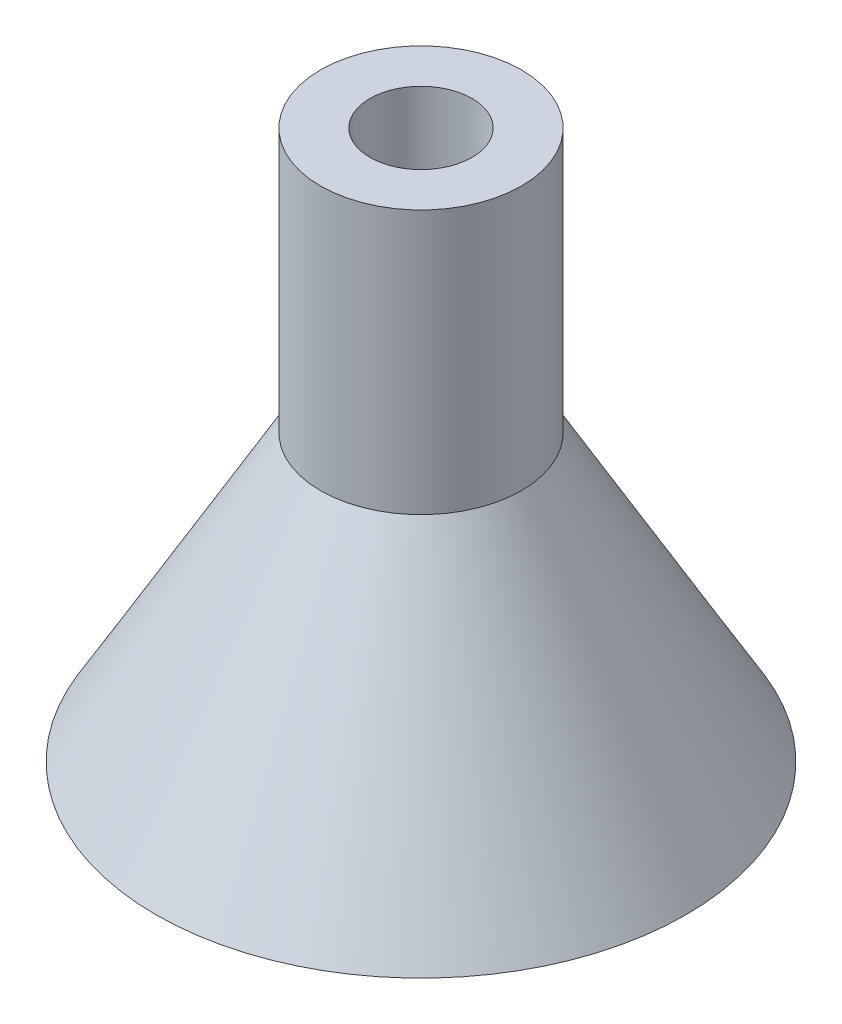
SolidWorks part; units mm, degrees
ref_plane "Front Plane" through (0, 0, 0) normal (0, 0, 1) x (1, 0, 0)
ref_plane "Top Plane" through (0, 0, 0) normal (0, 1, 0) x (1, 0, 0)
ref_plane "Right Plane" through (0, 0, 0) normal (1, 0, 0) x (0, 0, -1)
sketch "Sketch2" plane through (0, 0, 0) normal (0, 0, 1) x (1, 0, 0)
  line L0 (13.0723, 0) -> (16.0745, 0)
  line L1 (16.0745, 0) -> (6.096, 17.2833)
  line L2 (6.096, 17.2833) -> (6.096, 33.2833)
  line L3 (6.096, 33.2833) -> (3.096, 33.2833)
  line L4 (3.096, 33.2833) -> (3.096, 17.2795)
  line L5 (3.096, 17.2795) -> (13.0723, 0)
  line L6 (0, 0) -> (0, 50000) construction
  line L7 (-3.096, 17.2795) -> (-13.0723, 0) construction
  line L8 (-3.096, 33.2833) -> (-3.096, 17.2795) construction
  line L9 (-6.096, 33.2833) -> (-3.096, 33.2833) construction
  line L10 (-6.096, 17.2833) -> (-6.096, 33.2833) construction
  line L11 (-16.0745, 0) -> (-6.096, 17.2833) construction
  line L12 (-13.0723, 0) -> (-16.0745, 0) construction
  dimension "D1" = 3
  dimension "D2" = 2.6
  dimension "D3" = 12.192
  dimension "D5" = 16
  dimension "D6" = 30
revolve "Revolve1" add sketch "Sketch2" angle 360 about L6
